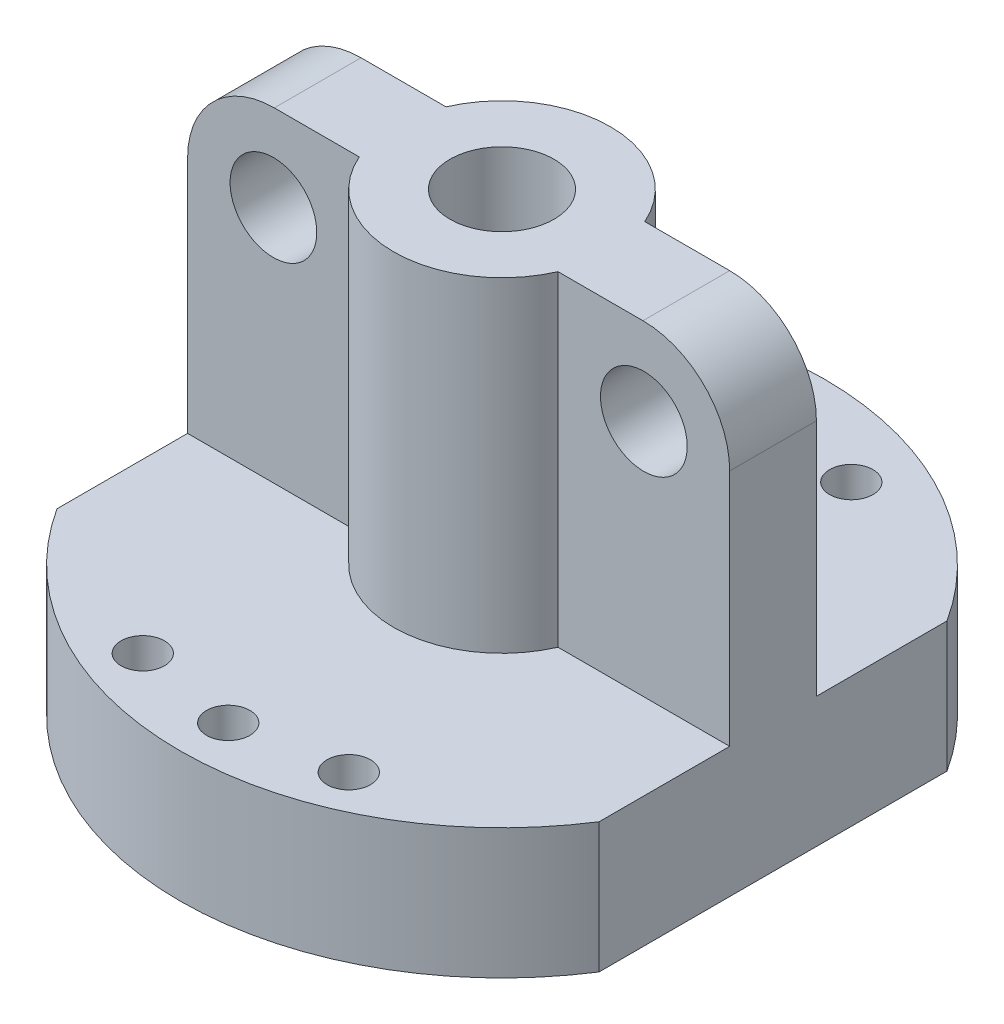
SolidWorks part; units mm, degrees
ref_plane "Front Plane" through (0, 0, 0) normal (0, 0, 1) x (1, 0, 0)
ref_plane "Top Plane" through (0, 0, 0) normal (0, 1, 0) x (1, 0, 0)
ref_plane "Right Plane" through (0, 0, 0) normal (1, 0, 0) x (0, 0, -1)
sketch "Sketch1" plane through (0, 6, 0) normal (0, 1, 0) x (1, 0, 0)
  circle A0 centre (1.5467, 37.6601) radius 29.705
  circle A1 centre (1.5467, 37.6601) radius 29.705 construction
extrude "Base" add sketch "Sketch1" along normal blind 12
sketch "Sketch2" plane through (0, 18, 0) normal (0, 1, 0) x (1, 0, 0)
  line L1 (-23.4533, 41.6601) -> (26.5467, 41.6601)
  line L2 (-23.4533, 41.6601) -> (-23.4533, 33.6601)
  line L3 (-23.4533, 33.6601) -> (26.5467, 33.6601)
  line L4 (26.5467, 41.6601) -> (26.5467, 33.6601)
  circle A0 centre (1.5467, 37.6601) radius 10
  point P7 (26.5467, 37.6601)
  point P8 (1.5467, 41.6601)
  dimension "D1" = 20
  dimension "D2" = 8
  dimension "D3" = 50
extrude "Support Shape" add sketch "Sketch2" along normal blind 30 contours A0 L1 L2 L3 | L1 A0 | L3 A0 L1 | L3 A0 | A0 L3 L4 L1
sketch "Sketch3" plane through (0, 48, 0) normal (0, 1, 0) x (1, 0, 0)
  circle A0 centre (1.5467, 37.6601) radius 4.8
  dimension "D1" = 9.6
extrude "Pen Hole" cut sketch "Sketch3" against normal through all
sketch "Sketch5" plane through (0, 6, 0) normal (0, -1, 0) x (1, 0, 0)
  circle A0 centre (-7.9533, -14.0266) radius 2
  circle A1 centre (-7.9533, -14.0266) radius 2 construction
  circle A2 centre (1.5467, -12.4101) radius 2
  circle A3 centre (1.5467, -12.4101) radius 2 construction
  circle A4 centre (11.0467, -14.0266) radius 2
  circle A5 centre (11.0467, -14.0266) radius 2 construction
  circle A6 centre (11.0467, -60.3766) radius 2
  circle A7 centre (11.0467, -60.3766) radius 2 construction
  circle A8 centre (1.5467, -62.9101) radius 2
  circle A9 centre (-7.9533, -60.3766) radius 2
  circle A10 centre (-7.9533, -60.3766) radius 2 construction
  circle A11 centre (1.5467, -62.9101) radius 2 construction
extrude "Bolt Holes" cut sketch "Sketch5" against normal through all
sketch "Sketch8" plane through (0, 0, -33.6601) normal (0, 0, 1) x (1, 0, 0)
  line L0 (10.7118, 48) -> (26.5467, 48) construction
  line L1 (-7.6185, 48) -> (10.7118, 48) construction
  line L2 (1.5467, 48) -> (1.5467, -27.3438) construction
  circle A0 centre (18.6292, 40) radius 4
  circle A1 centre (-15.5359, 40) radius 4
  point P4 (18.6292, 48)
  dimension "D1" = 8
  dimension "D2" = 8
extrude "Elastic Holes" cut sketch "Sketch8" against normal up to next
fillet "Decorative Fillet" radius 8 2 edges at (26.5467, 48, -37.6601) (-23.4533, 48, -37.6601)
sketch "Sketch9" plane through (0, 18, 0) normal (0, 1, 0) x (1, 0, 0)
  line L1 (26.5467, 9.18) -> (39.5761, 9.18)
  line L2 (26.5467, 9.18) -> (26.5467, 65.2318)
  line L3 (26.5467, 65.2318) -> (39.5761, 65.2318)
  line L4 (39.5761, 9.18) -> (39.5761, 65.2318)
  line L5 (-23.4533, 9.18) -> (-34.661, 9.18)
  line L6 (-23.4533, 9.18) -> (-23.4533, 71.2885)
  line L7 (-23.4533, 71.2885) -> (-34.661, 71.2885)
  line L8 (-34.661, 9.18) -> (-34.661, 71.2885)
extrude "Decorative Cut" cut sketch "Sketch9" against normal through all
